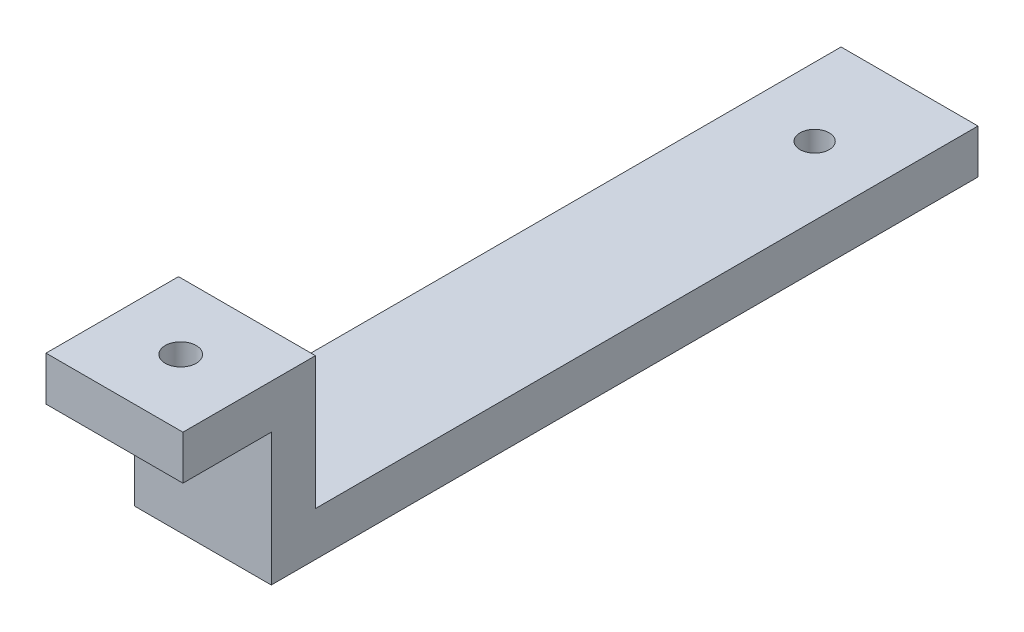
SolidWorks part; units mm, degrees
material "Galvanized Steel"
ref_plane "Front Plane" through (0, 0, 0) normal (0, 0, 1) x (1, 0, 0)
ref_plane "Top Plane" through (0, 0, 0) normal (0, 1, 0) x (1, 0, 0)
ref_plane "Right Plane" through (0, 0, 0) normal (1, 0, 0) x (0, 0, -1)
sketch "Sketch1" plane through (0, 0, 0) normal (1, 0, 0) x (0, 0, -1)
  line L0 (0, 0) -> (30, 0)
  line L1 (30, 0) -> (30, -29.972)
  line L2 (30, -29.972) -> (180, -29.972)
  dimension "D1" = 30
  dimension "D2" = 29.972
extrude "Extrude-Thin1" add sketch "Sketch1" along normal blind 31 thin contours L0 L1 L2
sketch "Sketch6" plane through (0, 0, 0) normal (0, 1, 0) x (1, 0, 0)
  line L0 (0, 0) -> (0, 30) construction
  line L2 (31, 30) -> (0, 30) construction
  circle A0 centre (15.5, 15) radius 3.5
  dimension "D1" = 7
  dimension "D2" = 15.5
  dimension "D3" = 15
extrude "Cut-Extrude1" cut sketch "Sketch6" against normal blind 10
sketch "Sketch7" plane through (0, -29.972, 0) normal (0, 1, 0) x (1, 0, 0)
  line L0 (31, 30) -> (0, 30) construction
  line L2 (0, 30) -> (0, 180) construction
  circle A0 centre (15.494, 158.524) radius 3.302
  dimension "D1" = 6.604
  dimension "D3" = 15.494
  dimension "D2" = 128.524
extrude "Cut-Extrude3" cut sketch "Sketch7" against normal blind 10.16
